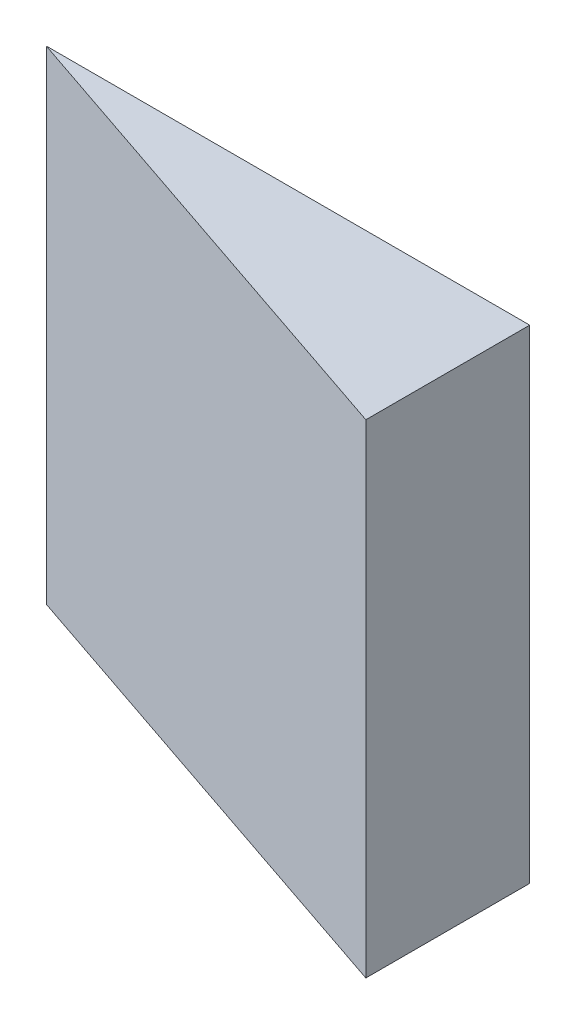
SolidWorks part; units mm, degrees
ref_plane "Front Plane" through (0, 0, 0) normal (0, 0, 1) x (1, 0, 0)
ref_plane "Top Plane" through (0, 0, 0) normal (0, 1, 0) x (1, 0, 0)
ref_plane "Right Plane" through (0, 0, 0) normal (1, 0, 0) x (0, 0, -1)
sketch "Sketch1" plane through (0, 0, 0) normal (0, 1, 0) x (1, 0, 0)
  line L0 (-9.9029, 34.1908) -> (65.0271, 34.1908)
  line L1 (65.0271, 34.1908) -> (65.0271, 8.7908)
  line L2 (-9.9029, 34.1908) -> (65.0271, 8.7908)
extrude "Boss-Extrude2" add sketch "Sketch1" along normal blind 74.93
